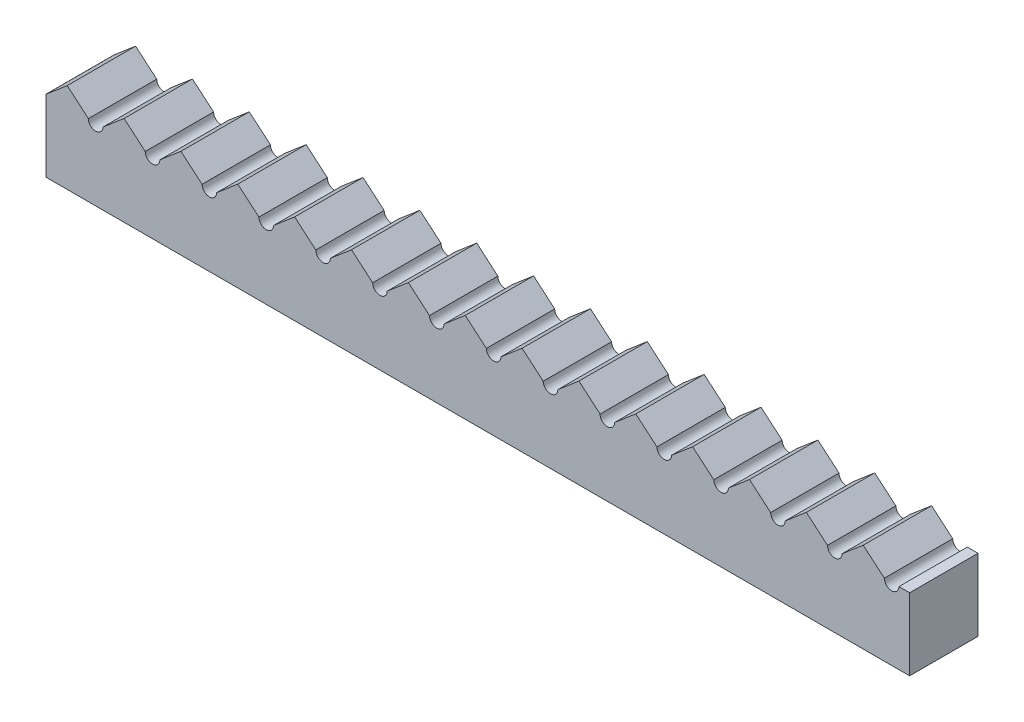
SolidWorks part; units mm, degrees
ref_plane "Front Plane" through (0, 0, 0) normal (0, 0, 1) x (1, 0, 0)
ref_plane "Top Plane" through (0, 0, 0) normal (0, 1, 0) x (1, 0, 0)
ref_plane "Right Plane" through (0, 0, 0) normal (1, 0, 0) x (0, 0, -1)
sketch "Sketch1" plane through (0, 0, 0) normal (0, 0, 1) x (1, 0, 0)
  line L1 (0, 0) -> (-304.8, 0)
  line L2 (0, 0) -> (0, -25.4)
  line L3 (0, -25.4) -> (-304.8, -25.4)
  line L4 (-304.8, 0) -> (-304.8, -25.4)
  dimension "D1" = 25.4
  dimension "D2" = 304.8
extrude "Boss-Extrude1" add sketch "Sketch1" along normal blind 24.13
sketch "Sketch3" plane through (0, 0, 24.13) normal (0, 0, 1) x (1, 0, 0)
  circle A0 centre (-26.416, 0) radius 2.5717
  circle A1 centre (-46.482, 0) radius 2.5717
  circle A2 centre (-66.548, 0) radius 2.5717
  circle A3 centre (-86.614, 0) radius 2.5717
  circle A4 centre (-106.68, 0) radius 2.5717
  circle A5 centre (-126.746, 0) radius 2.5717
  circle A6 centre (-146.812, 0) radius 2.5717
  circle A7 centre (-166.878, 0) radius 2.5718
  circle A8 centre (-186.944, 0) radius 2.5717
  circle A9 centre (-6.35, 0) radius 2.5717
  circle A10 centre (-207.01, 0) radius 2.5718
  circle A11 centre (-227.076, 0) radius 2.5717
  circle A12 centre (-247.142, 0) radius 2.5718
  circle A13 centre (-267.208, 0) radius 2.5718
  circle A14 centre (-287.274, 0) radius 2.5718
  dimension "D1" = 15
  dimension "D2" = 20.066
  dimension "D3" = 6.35
extrude "Cut-Extrude1" cut sketch "Sketch3" against normal blind 39.624
sketch "Sketch4" plane through (0, 0, 0) normal (0, 0, -1) x (-1, 0, 0)
  line L0 (8.9217, 0) -> (23.8443, 0)
  line L1 (23.8443, 0) -> (16.383, 6.35)
  line L2 (16.383, 6.35) -> (8.9217, 0)
  line L3 (28.9877, 0) -> (36.449, 6.35)
  line L4 (36.449, 6.35) -> (43.9103, 0)
  line L5 (28.9877, 0) -> (43.9103, 0)
  line L6 (56.515, 6.35) -> (63.9763, 0)
  line L7 (49.0537, 0) -> (63.9763, 0)
  line L8 (49.0537, 0) -> (56.515, 6.35)
  line L9 (76.581, 6.35) -> (84.0422, 0)
  line L10 (69.1197, 0) -> (84.0422, 0)
  line L11 (69.1197, 0) -> (76.581, 6.35)
  line L12 (96.647, 6.35) -> (104.1082, 0)
  line L13 (89.1857, 0) -> (104.1082, 0)
  line L14 (89.1857, 0) -> (96.647, 6.35)
  line L15 (116.713, 6.35) -> (124.1742, 0)
  line L16 (109.2517, 0) -> (124.1742, 0)
  line L17 (109.2517, 0) -> (116.713, 6.35)
  line L18 (136.779, 6.35) -> (144.2402, 0)
  line L19 (129.3177, 0) -> (144.2402, 0)
  line L20 (129.3177, 0) -> (136.779, 6.35)
  line L21 (156.845, 6.35) -> (164.3062, 0)
  line L22 (149.3837, 0) -> (164.3062, 0)
  line L23 (149.3837, 0) -> (156.845, 6.35)
  line L24 (176.911, 6.35) -> (184.3722, 0)
  line L25 (169.4497, 0) -> (184.3722, 0)
  line L26 (169.4497, 0) -> (176.911, 6.35)
  line L27 (196.977, 6.35) -> (204.4382, 0)
  line L28 (189.5157, 0) -> (204.4382, 0)
  line L29 (189.5157, 0) -> (196.977, 6.35)
  line L30 (217.043, 6.35) -> (224.5042, 0)
  line L31 (209.5817, 0) -> (224.5042, 0)
  line L32 (209.5817, 0) -> (217.043, 6.35)
  line L33 (237.109, 6.35) -> (244.5702, 0)
  line L34 (229.6477, 0) -> (244.5702, 0)
  line L35 (229.6477, 0) -> (237.109, 6.35)
  line L36 (257.175, 6.35) -> (264.6362, 0)
  line L37 (249.7137, 0) -> (264.6362, 0)
  line L38 (249.7137, 0) -> (257.175, 6.35)
  line L39 (277.241, 6.35) -> (284.7022, 0)
  line L40 (269.7797, 0) -> (284.7022, 0)
  line L41 (269.7797, 0) -> (277.241, 6.35)
  line L42 (297.307, 6.35) -> (304.7682, 0)
  line L43 (289.8457, 0) -> (304.7682, 0)
  line L44 (289.8457, 0) -> (297.307, 6.35)
  dimension "D1" = 6.35
  dimension "D2" = 6.35
  dimension "D3" = 14
extrude "Boss-Extrude2" add sketch "Sketch4" against normal up to surface (24.13 mm away) contours L41 L39 L40
